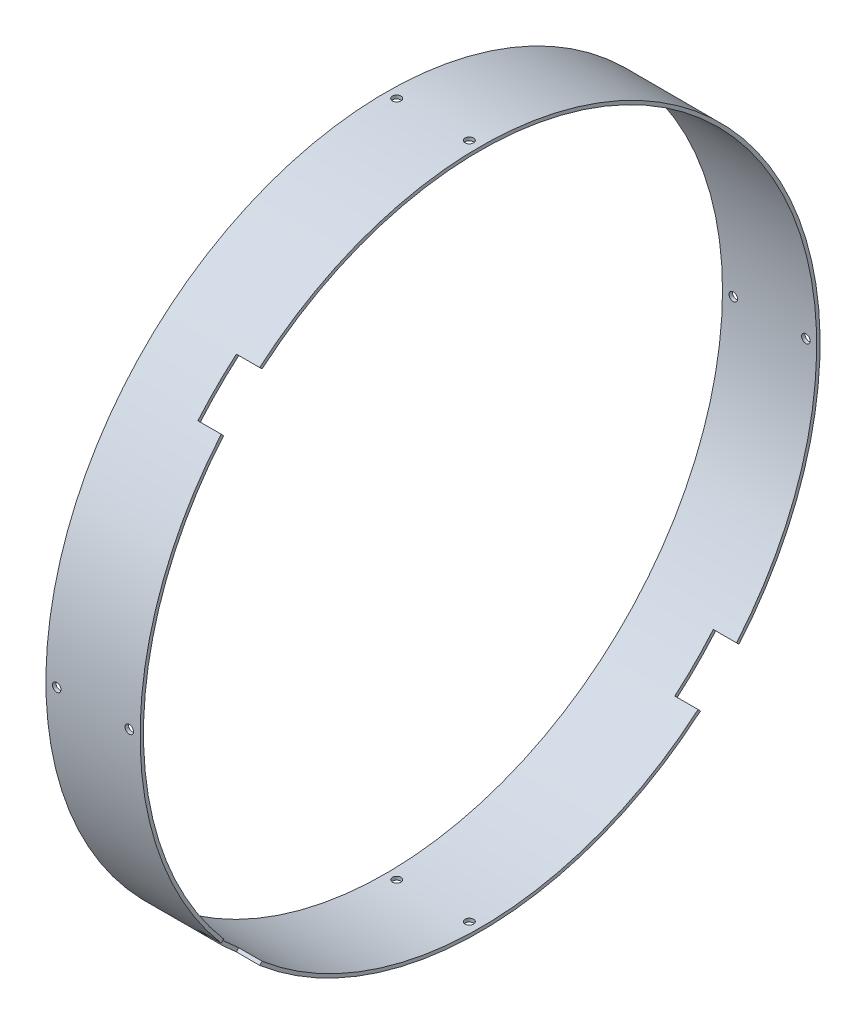
SolidWorks part; units mm, degrees
ref_plane "Front Plane" through (0, 0, 0) normal (0, 0, 1) x (1, 0, 0)
ref_plane "Top Plane" through (0, 0, 0) normal (0, 1, 0) x (1, 0, 0)
ref_plane "Right Plane" through (0, 0, 0) normal (1, 0, 0) x (0, 0, -1)
sketch "Sketch1" plane through (0, 0, 0) normal (1, 0, 0) x (0, 0, -1)
  circle A0 centre (0, 0) radius 100
  circle A1 centre (0, 0) radius 99
  dimension "D1" = 200
  dimension "D2" = 1
extrude "Boss-Extrude1" add sketch "Sketch1" along normal blind 27.7
ref_plane "Plane1" through (0, 0, 100) normal (0, 0, 1) x (1, 0, 0)
hole_wizard "Ø2.5mm Dowel Hole1" positions "Sketch2" profile "Sketch3" hole size "Ø2.5" standard "ANSI Metric" end condition through all
sketch "Sketch2" plane through (0, 0, 100) normal (0, 0, 1) x (1, 0, 0)
  line L0 (27.7, -100) -> (27.7, 100) construction
  line L1 (0, 100) -> (0, -100) construction
  point P0 (24.525, 0)
  point P2 (3.175, 0)
  dimension "D1" = 3.175
  dimension "D2" = 3.175
sketch "Sketch3" plane through (24.525, 0, 100) normal (1, 0, 0) x (0, -1, 0)
  line L0 (0, 0) -> (0, 200)
  line L1 (0, 200) -> (1.25, 200)
  line L2 (1.25, 200) -> (1.25, 0)
  line L5 (1.25, 0) -> (0, 0)
  line L11 (0, -6.35) -> (0, 107.95) construction
  dimension "Thru Hole Dia." = 2.5
  dimension "Thru Hole Depth" = 200
ref_plane "Plane2" through (0, 100, 0) normal (0, 1, 0) x (1, 0, 0)
hole_wizard "Ø2.5mm Dowel Hole2" positions "Sketch4" profile "Sketch5" hole size "Ø2.5" standard "ANSI Metric" end condition through all
sketch "Sketch4" plane through (0, 100, 0) normal (0, 1, 0) x (1, 0, 0)
  line L0 (27.7, -100) -> (27.7, 100) construction
  line L1 (0, 100) -> (0, -100) construction
  point P0 (24.525, 0)
  point P2 (3.175, 0)
  dimension "D1" = 3.175
  dimension "D2" = 3.175
sketch "Sketch5" plane through (24.525, 100, 0) normal (1, 0, 0) x (0, 0, 1)
  line L0 (0, 0) -> (0, 200)
  line L1 (0, 200) -> (1.25, 200)
  line L2 (1.25, 200) -> (1.25, 0)
  line L5 (1.25, 0) -> (0, 0)
  line L11 (0, -6.35) -> (0, 107.95) construction
  dimension "Thru Hole Dia." = 2.5
  dimension "Thru Hole Depth" = 200
ref_plane "Plane3" through (0, 0, 0) normal (0, 0.7071, -0.7071) x (-1, 0, 0)
sketch "Sketch6" plane through (0, 0, 0) normal (0, 0.7071, -0.7071) x (-1, 0, 0)
  line L0 (-21.35, 7.5) -> (-21.35, -7.5) construction
  line L1 (-21.35, 7.5) -> (-27.7, 7.5) construction
  line L2 (-21.35, -7.5) -> (-27.7, -7.5) construction
  line L3 (-27.7, 7.5) -> (-27.7, -7.5) construction
  line L5 (-27.7, 100) -> (-27.7, -100) construction
  line L6 (-20.85, 8) -> (-28.2, 8)
  line L7 (-28.2, 8) -> (-28.2, -8)
  line L8 (-20.85, -8) -> (-28.2, -8)
  line L9 (-20.85, 8) -> (-20.85, -8)
  point P0 (0, 0)
  point P6 (0, 0)
  point P7 (0, 0)
  point P9 (-27.7, 0)
  dimension "D1" = 15
  dimension "D2" = 6.35
  dimension "D3" = 0.5
extrude "Cut-Extrude1" cut sketch "Sketch6" against normal through all
ref_plane "Plane4" through (0, 0, 0) normal (0, 0.7071, 0.7071) x (-1, 0, 0)
sketch "Sketch7" plane through (0, 0, 0) normal (0, 0.7071, 0.7071) x (-1, 0, 0)
  line L0 (-27.7, 7.5) -> (-27.7, -7.5) construction
  line L1 (-27.7, 7.5) -> (-21.35, 7.5) construction
  line L2 (-27.7, -7.5) -> (-21.35, -7.5) construction
  line L3 (-21.35, 7.5) -> (-21.35, -7.5) construction
  line L4 (-27.7, 99.6795) -> (-27.7, -100) construction
  line L5 (-28.2, 8) -> (-20.85, 8)
  line L6 (-20.85, 8) -> (-20.85, -8)
  line L7 (-28.2, -8) -> (-20.85, -8)
  line L8 (-28.2, 8) -> (-28.2, -8)
  point P6 (-21.35, 0)
  dimension "D1" = 6.35
  dimension "D2" = 15
  dimension "D3" = 0.5
extrude "Cut-Extrude2" cut sketch "Sketch7" against normal through all both and the other way through all
